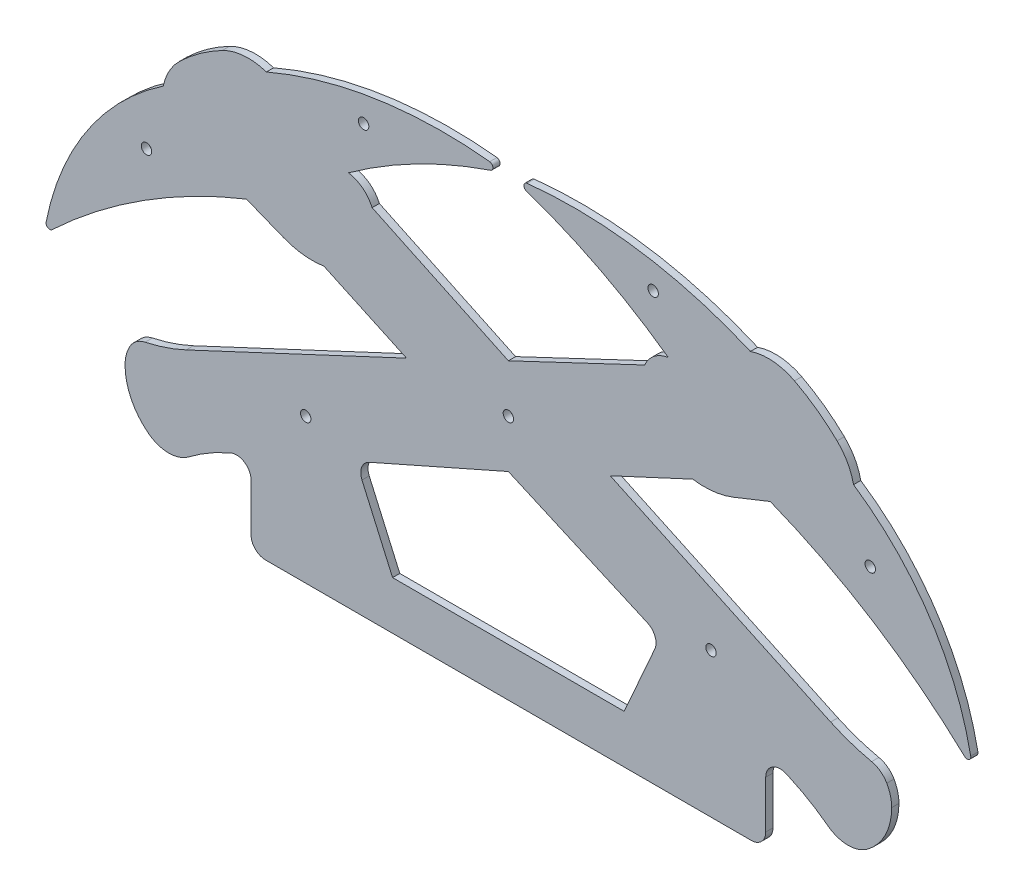
SolidWorks part; units mm, degrees
ref_plane "Front Plane" through (0, 0, 0) normal (0, 0, 1) x (1, 0, 0)
ref_plane "Top Plane" through (0, 0, 0) normal (0, 1, 0) x (1, 0, 0)
ref_plane "Right Plane" through (0, 0, 0) normal (1, 0, 0) x (0, 0, -1)
sketch "Sketch1" plane through (0, 0, 0) normal (0, 0, 1) x (1, 0, 0)
  line L0 (-7.456, 89.4504) -> (178.8798, 89.4504) construction
  line L1 (192.9838, 175.4412) -> (96.3096, 130.2274)
  line L2 (114.7894, 100.3711) -> (237.664, 154.6988)
  line L3 (237.664, 196.7769) -> (177.8969, 225.0593)
  line L4 (192.9838, 175.4412) -> (156.7682, 192.2435)
  line L5 (122.7816, 200.7534) -> (138.9317, 194.3128)
  line L6 (237.664, 267.4202) -> (237.664, 154.6988) construction
  line L7 (352.5463, 200.7534) -> (336.3962, 194.3128)
  line L8 (282.3442, 175.4412) -> (318.5597, 192.2435)
  line L9 (237.664, 196.7769) -> (297.431, 225.0593)
  line L10 (360.5386, 100.3711) -> (237.664, 154.6988)
  line L11 (282.3442, 175.4412) -> (379.0184, 130.2274)
  arc A0 (96.3096, 130.2274) -> (78.3175, 124.1761) centre (60.6568, 206.4587) cw
  arc A1 (78.3175, 124.1761) -> (71.6647, 119.2855) centre (80.4305, 114.3314) ccw
  arc A2 (71.6647, 119.2855) -> (69.5125, 111.0967) centre (86.1425, 111.1032) ccw
  arc A3 (69.5125, 111.0967) -> (79.9352, 90.1473) centre (95.7986, 111.107) ccw
  arc A4 (79.9352, 90.1473) -> (97.4231, 90.1473) centre (88.6791, 101.7003) ccw
  arc A5 (97.4231, 90.1473) -> (114.7894, 100.3711) centre (150.0582, 20.6026) cw
  arc A6 (156.7682, 192.2435) -> (138.9317, 194.3128) centre (151.678, 226.2747) cw
  arc A7 (307.7941, 233.1357) -> (297.431, 225.0593) centre (310.0373, 219.5707) ccw
  arc A8 (122.7816, 200.7534) -> (34.0226, 143.1916) centre (222.9286, -50.884) ccw
  arc A9 (34.0226, 143.1916) -> (86.2485, 225.4232) centre (153.9924, 124.6982) cw
  arc A10 (86.2485, 225.4232) -> (93.4631, 238.4495) centre (110.9979, 220.2268) cw
  arc A11 (93.4631, 238.4495) -> (112.1407, 251.9085) centre (149.9585, 179.7377) cw
  arc A12 (112.1407, 251.9085) -> (131.4929, 253.4154) centre (123.5746, 230.0882) cw
  arc A15 (167.5338, 233.1357) -> (177.8969, 225.0593) centre (165.2907, 219.5707) cw
  arc A18 (363.1873, 251.9085) -> (343.835, 253.4154) centre (351.7533, 230.0882) ccw
  arc A19 (381.8648, 238.4495) -> (363.1873, 251.9085) centre (325.3694, 179.7377) ccw
  arc A20 (389.0794, 225.4232) -> (381.8648, 238.4495) centre (364.3301, 220.2268) ccw
  arc A21 (441.3053, 143.1916) -> (389.0794, 225.4232) centre (321.3356, 124.6982) ccw
  arc A22 (352.5463, 200.7534) -> (441.3053, 143.1916) centre (252.3994, -50.884) cw
  arc A23 (318.5597, 192.2435) -> (336.3962, 194.3128) centre (323.6499, 226.2747) ccw
  arc A24 (377.9048, 90.1473) -> (360.5386, 100.3711) centre (325.2698, 20.6026) ccw
  arc A25 (395.3928, 90.1473) -> (377.9048, 90.1473) centre (386.6488, 101.7003) cw
  arc A26 (405.8155, 111.0967) -> (395.3928, 90.1473) centre (379.5293, 111.107) cw
  arc A27 (403.6633, 119.2855) -> (405.8155, 111.0967) centre (389.1855, 111.1032) cw
  arc A28 (397.0105, 124.1761) -> (403.6633, 119.2855) centre (394.8975, 114.3314) cw
  arc A29 (379.0184, 130.2274) -> (397.0105, 124.1761) centre (414.6711, 206.4587) ccw
  arc A30 (167.5338, 233.1357) -> (236.5684, 267.4202) centre (306.6135, 39.7332) cw
  arc A31 (131.4929, 253.4154) -> (236.5684, 267.4202) centre (208.8369, 74.3006) cw
  arc A32 (307.7941, 233.1357) -> (238.7596, 267.4202) centre (168.7145, 39.7332) ccw
  arc A33 (343.835, 253.4154) -> (238.7596, 267.4202) centre (266.491, 74.3006) ccw
  point P72 (236.5684, 267.4202)
extrude "Boss-Extrude1" add sketch "Sketch1" along normal blind 3.175
sketch "Sketch2" plane through (0, 0, 0) normal (0, 0, 1) x (1, 0, 0)
  line L0 (124.7751, 104.7862) -> (124.7751, 67.8337)
  line L1 (124.7751, 67.8337) -> (350.5529, 67.8337)
  line L2 (237.664, 89.0003) -> (237.664, 67.8337) construction
  line L3 (288.464, 89.0003) -> (186.864, 89.0003)
  line L4 (186.864, 89.0003) -> (170.8729, 125.1679)
  line L5 (114.7894, 100.3711) -> (237.664, 154.6988) construction
  line L6 (124.7751, 104.7862) -> (170.8729, 125.1679)
  line L7 (350.5529, 104.7862) -> (304.4551, 125.1679)
  line L8 (288.464, 89.0003) -> (304.4551, 125.1679)
  line L9 (350.5529, 104.7862) -> (350.5529, 67.8337)
  line L10 (237.664, 154.6988) -> (360.5386, 100.3711) construction
  arc A3 (79.9352, 90.1473) -> (97.4231, 90.1473) centre (88.6791, 101.7003) ccw construction
  dimension "D1" = 21.1667
  dimension "D2" = 12.7
  dimension "D3" = 225.7778
  dimension "D4" = 50.8
extrude "Boss-Extrude2" add sketch "Sketch2" along normal up to surface (3.175 mm away) up to face at (237.664, 178.0943, 3.175)
fillet "Fillet1" radius 6.35 6 edges at (350.5529, 67.8337, 1.5875) (304.4551, 125.1679, 1.5875) (170.8729, 125.1679, 1.5875) (124.7751, 67.8337, 1.5875) (350.5529, 104.7862, 1.5875) (124.7751, 104.7862, 1.5875)
sketch "Sketch3" plane through (0, 0, 3.175) normal (0, 0, 1) x (1, 0, 0)
  line L0 (237.664, 196.7769) -> (237.664, 154.6988) construction
  line L1 (78.914, 197.9629) -> (396.414, 197.9629) construction
  line L2 (301.164, 255.1129) -> (174.164, 255.1129) construction
  line L3 (148.764, 131.2879) -> (326.564, 131.2879) construction
  circle A0 centre (237.664, 175.7379) radius 2.286
  circle A1 centre (78.914, 197.9629) radius 2.286
  circle A2 centre (174.164, 255.1129) radius 2.286
  circle A3 centre (301.164, 255.1129) radius 2.286
  circle A4 centre (396.414, 197.9629) radius 2.286
  circle A5 centre (148.764, 131.2879) radius 2.286
  circle A6 centre (326.564, 131.2879) radius 2.286
  point P14 (237.664, 255.1129)
  point P15 (237.664, 197.9629)
  point P18 (237.664, 131.2879)
  dimension "D1" = 4.572
  dimension "D2" = 127
  dimension "D3" = 317.5
  dimension "D4" = 22.225
  dimension "D5" = 79.375
  dimension "1.75" = 44.45
  dimension "D7" = 177.8
extrude "Cut-Extrude1" cut sketch "Sketch3" against normal through all
fillet "Fillet2" radius 1.5875 4 edges at (34.0226, 143.1916, 1.5875) (441.3053, 143.1916, 1.5875) (238.7596, 267.4202, 1.5875) (236.5684, 267.4202, 1.5875)
scale "Scale4" scale about centroid uniform scaling yes scale factor 0.9
scale "Scale5" [suppressed]
